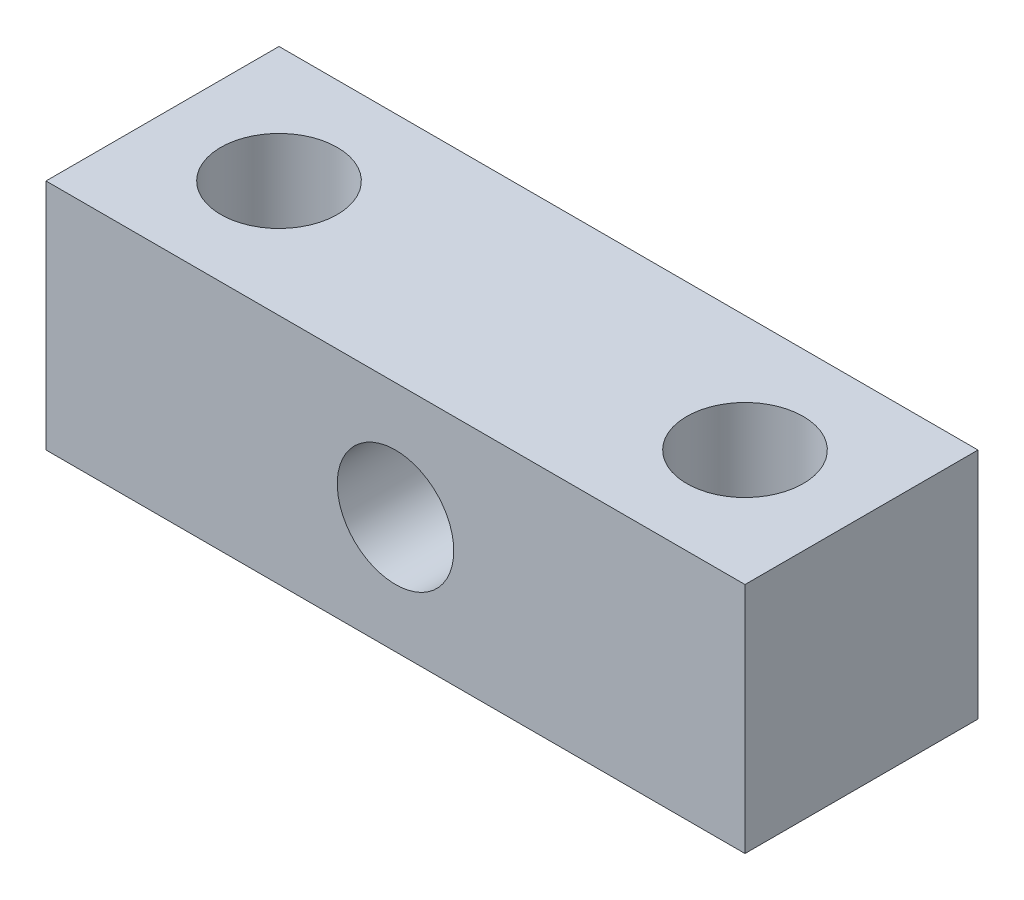
SolidWorks part; units mm, degrees
material "自訂玻璃纖維"
ref_plane "前基準面" through (0, 0, 0) normal (0, 0, 1) x (1, 0, 0)
ref_plane "上基準面" through (0, 0, 0) normal (0, 1, 0) x (1, 0, 0)
ref_plane "右基準面" through (0, 0, 0) normal (1, 0, 0) x (0, 0, -1)
sketch "草圖1" plane through (0, 0, 0) normal (0, 0, 1) x (1, 0, 0)
  line L1 (-6.1941, 3.085) -> (5.8059, 3.085)
  line L2 (-6.1941, 3.085) -> (-6.1941, -0.915)
  line L3 (-6.1941, -0.915) -> (5.8059, -0.915)
  line L4 (5.8059, 3.085) -> (5.8059, -0.915)
  dimension "D1" = 12
  dimension "D2" = 4
extrude "填料-伸長1" add sketch "草圖1" along normal blind 4
sketch "草圖2" plane through (0, -0.915, 0) normal (0, -1, 0) x (1, 0, 0)
  line L0 (-6.1941, 4) -> (5.8059, 4) construction
  line L1 (-6.1941, 4) -> (-6.1941, 0) construction
  line L2 (5.8059, 4) -> (5.8059, 0) construction
  circle A0 centre (-4.1941, 2) radius 1
  circle A1 centre (3.8059, 2) radius 1
  dimension "D1" = 2
  dimension "D4" = 2
  dimension "D2" = 2
  dimension "D3" = 2
  dimension "D5" = 2
  dimension "D6" = 2
extrude "除料-伸長1" cut sketch "草圖2" against normal blind 11
sketch "草圖3" plane through (0, 0, 4) normal (0, 0, 1) x (1, 0, 0)
  line L0 (-6.1941, -0.915) -> (5.8059, -0.915) construction
  line L1 (-6.1941, 3.085) -> (-6.1941, -0.915) construction
  circle A0 centre (-0.1941, 1.085) radius 1
  dimension "D1" = 2
  dimension "D2" = 2
  dimension "D3" = 6
extrude "除料-伸長2" cut sketch "草圖3" against normal blind 11
